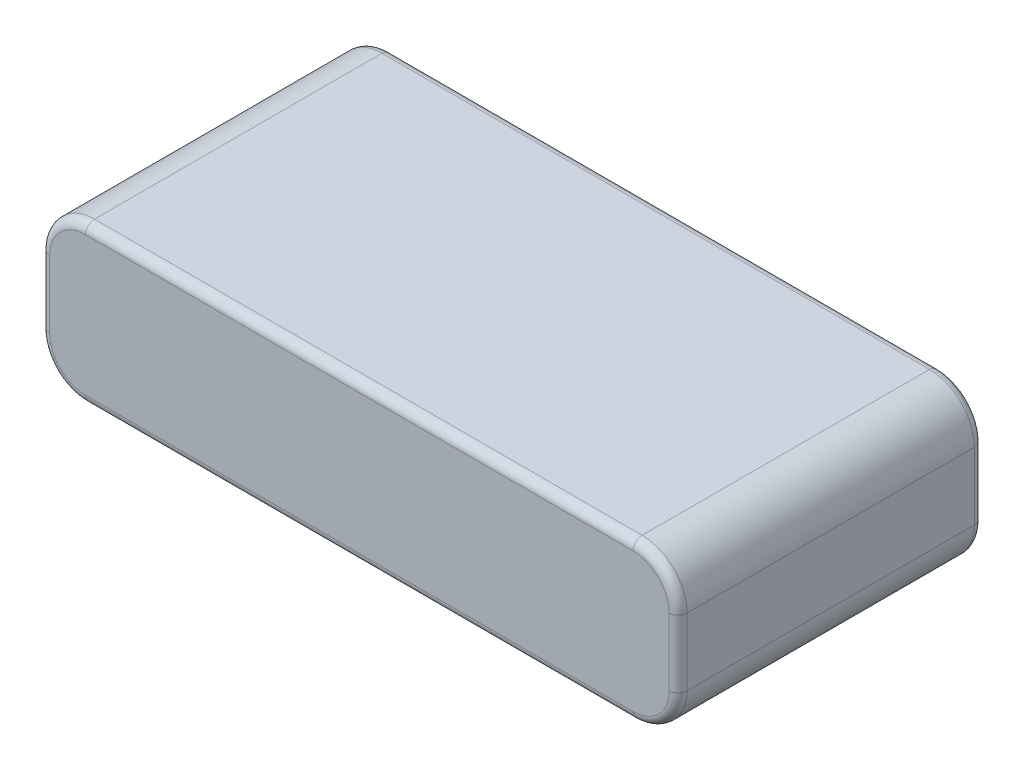
SolidWorks part; units mm, degrees
ref_plane "Front Plane" through (0, 0, 0) normal (0, 0, 1) x (1, 0, 0)
ref_plane "Top Plane" through (0, 0, 0) normal (0, 1, 0) x (1, 0, 0)
ref_plane "Right Plane" through (0, 0, 0) normal (1, 0, 0) x (0, 0, -1)
sketch "Sketch1" plane through (0, 0, 0) normal (0, 1, 0) x (1, 0, 0)
  line L1 (-35.5, 17) -> (35.5, 17)
  line L2 (-35.5, 17) -> (-35.5, -17)
  line L3 (-35.5, -17) -> (35.5, -17)
  line L4 (35.5, 17) -> (35.5, -17)
  line L5 (-35.5, 17) -> (35.5, -17) construction
  line L6 (-35.5, -17) -> (35.5, 17) construction
  point P0 (0, 0)
  dimension "D1" = 71
  dimension "D2" = 34
extrude "Boss-Extrude1" add sketch "Sketch1" along normal blind 17.5
fillet "Fillet1" radius 5 4 edges at (-35.5, 0, 0) (35.5, 0, 0) (35.5, 17.5, 0) (-35.5, 17.5, 0)
fillet "Fillet2" radius 1 16 edges at (34.0355, 16.0355, -17) (35.5, 8.75, -17) (34.0355, 1.4645, -17) (0, 0, -17) (-34.0355, 1.4645, -17) (-35.5, 8.75, -17) (-34.0355, 16.0355, -17) (-34.0355, 16.0355, 17) (-35.5, 8.75, 17) (-34.0355, 1.4645, 17) (0, 0, 17) (34.0355, 1.4645, 17) (35.5, 8.75, 17) (34.0355, 16.0355, 17) (0, 17.5, -17) (0, 17.5, 17)
